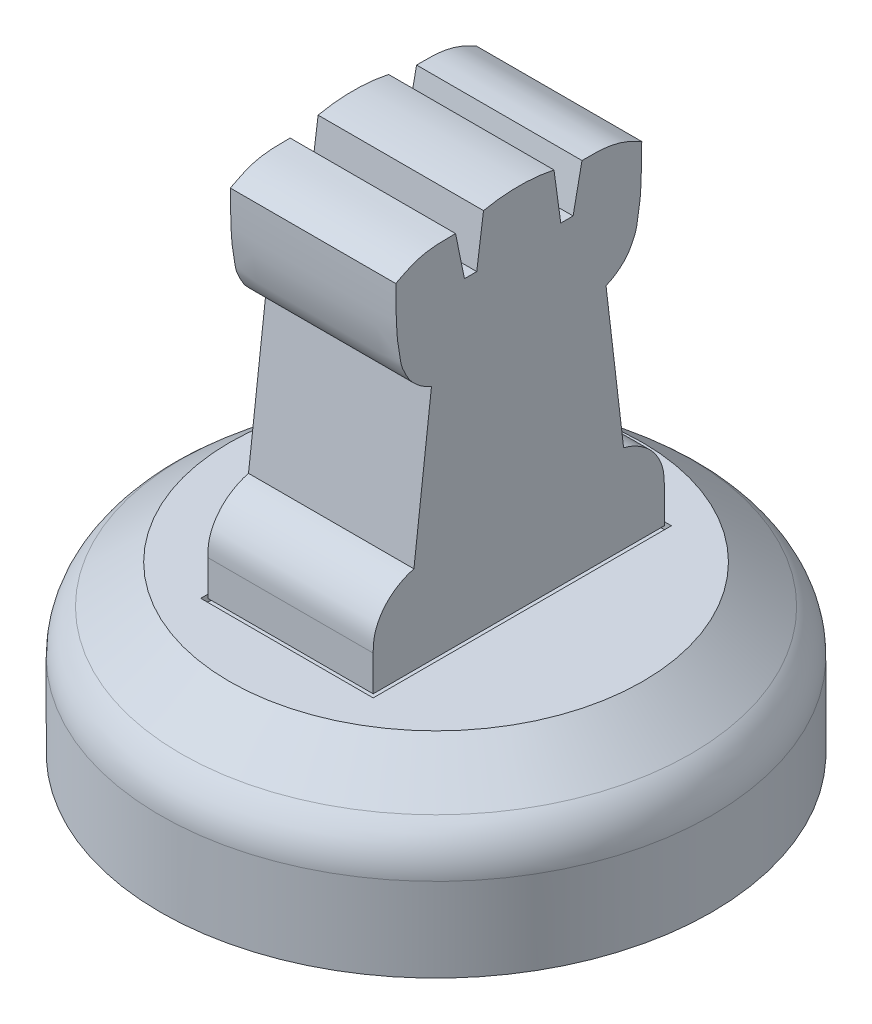
SolidWorks part; units mm, degrees
ref_plane "Front" through (0, 0, 0) normal (0, 0, 1) x (1, 0, 0)
ref_plane "Top" through (0, 0, 0) normal (0, 1, 0) x (1, 0, 0)
ref_plane "Right" through (0, 0, 0) normal (1, 0, 0) x (0, 0, -1)
sketch "Sketch1" plane through (0, 0, 0) normal (0, 1, 0) x (1, 0, 0)
  circle A0 centre (0, 0) radius 15.875
  dimension "D1" = 31.75
extrude "Boss-Extrude1" add sketch "Sketch1" along normal blind 6.35
sketch "Sketch2" plane through (0, 0, 0) normal (0, 0, 1) x (1, 0, 0)
  line L0 (-15.875, 6.35) -> (-11.9062, 9.525)
  line L1 (-11.9062, 9.525) -> (0, 9.525)
  line L2 (0, 9.525) -> (0, 6.35)
  line L3 (15.875, 6.35) -> (-15.875, 6.35) construction
  line L4 (0, 6.35) -> (-15.875, 6.35)
  line L5 (-15.875, 0) -> (15.875, 0) construction
  dimension "D1" = 3.9688
  dimension "D2" = 9.525
revolve "Revolve1" add sketch "Sketch2" angle 360 about L2
fillet "Fillet1" radius 3.175 1 edges at (0, 6.35, 15.875)
sketch "Sketch3" plane through (0, 0, 0) normal (0, -1, 0) x (1, 0, 0)
  line L1 (-6.4516, -9.6266) -> (6.4516, -9.6266)
  line L2 (-6.4516, -9.6266) -> (-6.4516, 9.6266)
  line L3 (-6.4516, 9.6266) -> (6.4516, 9.6266)
  line L4 (6.4516, -9.6266) -> (6.4516, 9.6266)
  line L5 (-6.4516, -9.6266) -> (6.4516, 9.6266) construction
  line L6 (-6.4516, 9.6266) -> (6.4516, -9.6266) construction
  point P0 (0, 0)
  dimension "D1" = 19.2532
  dimension "D2" = 12.9032
extrude "Cut-Extrude1" cut sketch "Sketch3" against normal blind 4.7625
hole_wizard "#6 (0.204) Diameter Hole1" positions "Sketch4" profile "Sketch5" hole size "#6" standard "ANSI Inch" end condition through all
sketch "Sketch4" plane through (0, 4.7625, 0) normal (0, -1, 0) x (-1, 0, 0)
  point P0 (0, 0)
sketch "Sketch5" plane through (0, 4.7625, 0) normal (1, 0, 0) x (0, 0, -1)
  line L0 (0, 0) -> (0, 4.7625)
  line L1 (0, 4.7625) -> (2.5908, 4.7625)
  line L2 (2.5908, 4.7625) -> (2.5908, 0)
  line L5 (2.5908, 0) -> (0, 0)
  line L11 (0, -6.35) -> (0, 107.95) construction
  dimension "Thru Hole Dia." = 5.1816
  dimension "Thru Hole Depth" = 4.7625
sketch "Sketch6" plane through (0, 0, 0) normal (1, 0, 0) x (0, 0, -1)
  line L0 (28.5697, 134.985) -> (199.2363, 134.985) construction
  line L1 (-8.382, 9.525) -> (8.382, 9.525)
  line L2 (11.9062, 9.525) -> (-11.9062, 9.525) construction
  line L3 (-8.382, 9.525) -> (-8.382, 11.557)
  line L4 (8.382, 9.525) -> (8.382, 11.557)
  line L5 (-6.0372, 14.586) -> (-5.0245, 23.1804)
  line L6 (-3.6404, 30.1091) -> (-3.1281, 27.6006)
  line L7 (-3.1281, 27.6006) -> (-2.4183, 27.6006)
  line L8 (-2.4183, 27.6006) -> (-2.0286, 30.4452)
  line L9 (0, 50) -> (0, -50) construction
  line L10 (6.0372, 14.586) -> (5.0245, 23.1804)
  line L11 (3.6404, 30.1091) -> (3.1281, 27.6006)
  line L12 (3.1281, 27.6006) -> (2.4183, 27.6006)
  line L13 (2.4183, 27.6006) -> (2.0286, 30.4452)
  arc A0 (-2.0286, 30.4452) -> (2.0286, 30.4452) centre (0, 20.7729) cw
  spline S0 degree 3 poles (-8.382, 11.557) (-8.382, 11.858) (-8.3442, 12.4541) (-7.9852, 13.2454) (-7.4863, 13.8333) (-6.8386, 14.2952) (-6.3494, 14.5109) (-6.0372, 14.586) knots 0 0 0 0 0.216472 0.427785 0.616071 0.768549 1 1 1 1
  spline S1 degree 3 poles (-5.0245, 23.1804) (-5.3071, 23.2805) (-5.769, 23.5748) (-6.2766, 24.0723) (-6.5477, 24.583) (-6.7691, 25.0488) (-6.8654, 25.7388) (-7.009, 26.5066) (-7.0669, 27.7617) (-7.0859, 28.6809) (-7.0829, 29.3361) knots 0 0 0 0 0.12872 0.235852 0.302405 0.378129 0.457345 0.601695 0.716525 1 1 1 1
  spline S2 degree 3 poles (-7.0829, 29.3361) (-6.8388, 29.4557) (-6.4682, 29.6575) (-5.9073, 29.8821) (-5.0129, 30.1195) (-4.2266, 30.1082) (-3.6404, 30.1091) knots 0 0 0 0 0.227779 0.352762 0.505199 1 1 1 1
  spline S3 degree 3 poles (8.382, 11.557) (8.382, 11.858) (8.3442, 12.4541) (7.9852, 13.2454) (7.4863, 13.8333) (6.8386, 14.2952) (6.3494, 14.5109) (6.0372, 14.586) knots 0 0 0 0 0.216472 0.427785 0.616071 0.768549 1 1 1 1
  spline S4 degree 3 poles (5.0245, 23.1804) (5.3071, 23.2805) (5.769, 23.5748) (6.2766, 24.0723) (6.5477, 24.583) (6.7691, 25.0488) (6.8654, 25.7388) (7.009, 26.5066) (7.0669, 27.7617) (7.0859, 28.6809) (7.0829, 29.3361) knots 0 0 0 0 0.12872 0.235852 0.302405 0.378129 0.457345 0.601695 0.716525 1 1 1 1
  spline S5 degree 3 poles (7.0829, 29.3361) (6.8388, 29.4557) (6.4682, 29.6575) (5.9073, 29.8821) (5.0129, 30.1195) (4.2266, 30.1082) (3.6404, 30.1091) knots 0 0 0 0 0.227779 0.352762 0.505199 1 1 1 1
  point P6 (0, 9.525)
  dimension "D1" = 16.764
  dimension "D2" = 2.032
extrude "Boss-Extrude2" add sketch "Sketch6" along normal mid plane 9.525 separate body
sketch "Sketch7" plane through (0, 9.525, 0) normal (0, 1, 0) x (1, 0, 0)
  line L14 (-4.9657, -8.5852) -> (4.9657, -8.5852)
  line L15 (-4.9657, 8.5852) -> (-4.9657, -8.5852)
  line L16 (4.9657, 8.5852) -> (-4.9657, 8.5852)
  line L17 (4.9657, -8.5852) -> (4.9657, 8.5852)
  line L18 (-4.9657, -8.5852) -> (4.9657, -8.5852)
  line L19 (-4.9657, 8.5852) -> (-4.9657, -8.5852)
  line L20 (4.9657, 8.5852) -> (-4.9657, 8.5852)
  line L21 (4.9657, -8.5852) -> (4.9657, 8.5852)
  dimension "D1" = 0.2032
extrude "Cut-Extrude2" cut sketch "Sketch7" against normal blind 0.3969
